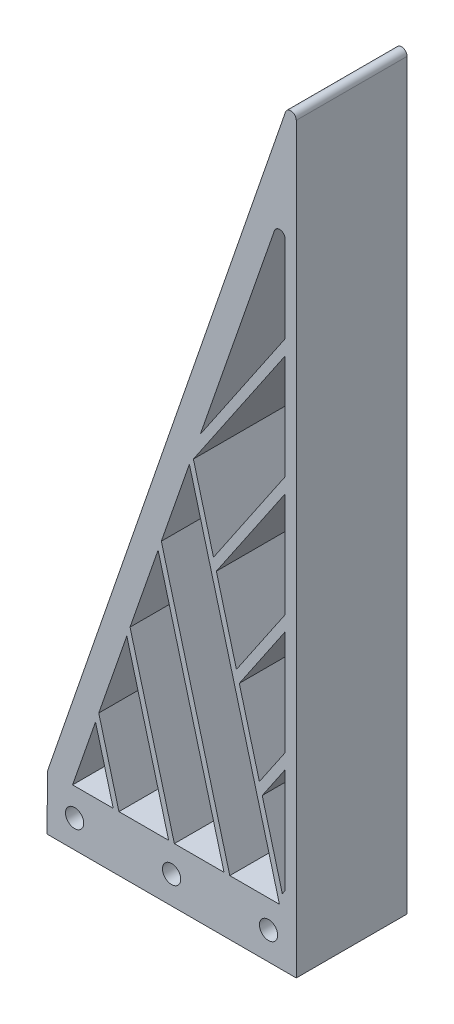
SolidWorks part; units mm, degrees
material "Custom Plastic"
ref_plane "Front Plane" through (0, 0, 0) normal (0, 0, 1) x (1, 0, 0)
ref_plane "Top Plane" through (0, 0, 0) normal (0, 1, 0) x (1, 0, 0)
ref_plane "Right Plane" through (0, 0, 0) normal (1, 0, 0) x (0, 0, -1)
sketch "Sketch1" plane through (0, 0, 0) normal (0, 1, 0) x (1, 0, 0)
  line L1 (-9.5, 8) -> (9.5, 8) construction
  line L2 (-9.5, 8) -> (-9.5, -8) construction
  line L3 (-9.5, -8) -> (9.5, -8) construction
  line L4 (9.5, 8) -> (9.5, -8) construction
  line L5 (-9.5, 8) -> (9.5, -8) construction
  line L6 (-9.5, -8) -> (9.5, 8) construction
  line L7 (12, 10.5) -> (-12, 10.5)
  line L8 (12, 10.5) -> (12, -10.5)
  line L9 (12, -10.5) -> (-12, -10.5)
  line L10 (-12, 10.5) -> (-12, -10.5)
  line L11 (12, 10.5) -> (-12, -10.5) construction
  line L12 (12, -10.5) -> (-12, 10.5) construction
  circle A0 centre (-9.5, 8) radius 1.625
  circle A1 centre (9.5, 8) radius 1.625
  circle A2 centre (9.5, -8) radius 1.625
  circle A3 centre (-9.5, -8) radius 1.625
  point P0 (0, 0)
  point P10 (0, 0)
  dimension "D3" = 3.25
  dimension "D1" = 24
  dimension "D2" = 21
  dimension "D4" = 19
  dimension "D5" = 16
extrude "Boss-Extrude1" [suppressed] add sketch "Sketch1" along normal blind 7.5
sketch "Sketch5" plane through (0, 0, 0) normal (0, 0, 1) x (1, 0, 0)
  line L0 (0, 0) -> (0, 167.0412)
  line L1 (-45, 0) -> (0, 0)
  line L2 (-1.6, 10) -> (-39.8602, 10)
  line L98 (-1.6, 10) -> (-1.6, 153.5644)
  line L99 (-45, 0) -> (-45, 5) construction
  line L102 (-39.9651, 5) -> (-5, 5) construction
  line L103 (-5, 5) -> (-5, 154.3355) construction
  line L104 (0, 0) -> (0, 175) construction
  arc A1 (-3.7727, 167.9673) -> (-45, 0) centre (317.7778, 0) ccw
  arc A24 (-5, 154.3355) -> (-39.8602, 10) centre (317.7778, 0) ccw
  arc A25 (-5, 154.3355) -> (-39.9651, 5) centre (317.7778, 0) ccw construction
  arc A26 (-1.6, 153.5644) -> (-5, 154.3355) centre (-3.3874, 153.5644) ccw
  arc A27 (0, 175) -> (-45, 0) centre (317.7778, 0) ccw construction
  arc A28 (0, 167.0412) -> (-3.7727, 167.9673) centre (-2, 167.0412) ccw
  point P16 (0, 175)
  dimension "D7" = 2
  dimension "D2" = 175
  dimension "D5" = 10
  dimension "D6" = 1.6
  dimension "D1" = 5
  dimension "D3" = 45
  dimension "D4" = 5
extrude "Boss-Extrude4" add sketch "Sketch5" along normal blind 20
sketch "Sketch10" plane through (0, 0, 20) normal (0, 0, 1) x (1, 0, 0)
  line L0 (-39.6854, 15) -> (-1.6, 15)
  line L1 (-1.6, 10) -> (-1.6, 153.5644) construction
  line L2 (-1.6, 16.6) -> (-39.6147, 16.6)
  line L3 (-39.8602, 10) -> (-1.6, 10) construction
  line L4 (0, 10) -> (75, 10) construction
  line L5 (0, 0) -> (0, 167.0412) construction
  line L6 (-38.5345, 26.9605) -> (-0.6577, 22.9795)
  line L7 (-0.4905, 24.5707) -> (-38.2969, 28.5443)
  line L8 (-36.1397, 38.7352) -> (1.1135, 30.8168)
  line L9 (1.4461, 32.3818) -> (-35.7379, 40.2855)
  line L10 (-32.5272, 50.195) -> (3.6942, 38.426)
  line L11 (4.1886, 39.9477) -> (-31.9655, 51.6949)
  line L12 (-27.7367, 61.2145) -> (7.0561, 45.7238)
  line L13 (7.7069, 47.1854) -> (-27.0213, 62.6474)
  line L14 (-21.8205, 71.6728) -> (11.1625, 52.6301)
  line L15 (11.9625, 54.0158) -> (-20.9592, 73.0231)
  line L20 (0, 68.0707) -> (75, 10) construction
  line L21 (-1.6, 69.3095) -> (-28.4662, 90.1114)
  line L22 (-1.6, 70.9537) -> (-28.1077, 91.4779)
  line L23 (3.8607, 75.76) -> (-21.0903, 98.8242)
  line L24 (4.0039, 77.3979) -> (-20.614, 100.1543)
  line L25 (9.8627, 81.7099) -> (-12.9831, 106.861)
  line L26 (10.1482, 83.3291) -> (-12.3927, 108.1445)
  line L27 (16.3605, 87.1142) -> (-4.2063, 114.1607)
  line L28 (16.7861, 88.7023) -> (-3.5063, 115.3878)
  line L29 (23.3046, 91.9315) -> (5.1733, 120.6676)
  line L30 (23.8669, 93.4765) -> (5.9776, 121.8291)
  arc A0 (-5, 154.3355) -> (-39.8602, 10) centre (317.7778, 0) ccw construction
  arc A1 (-5, 154.3355) -> (-39.8602, 10) centre (317.7778, 0) ccw
  point P54 (75, 10)
  point P67 (75, 10)
  dimension "D1" = 1.6
  dimension "D2" = 5
  dimension "D5" = 6
  dimension "D6" = 1.3
  dimension "D9" = 5
  dimension "D7" = 7.75
  dimension "D3" = 144.3355
  dimension "D4" = 6
  dimension "D8" = 5
sketch "Sketch11" plane through (0, 0, 20) normal (0, 0, 1) x (1, 0, 0)
  line L0 (-39.6854, 15) -> (-1.6, 15)
  line L1 (-1.6, 10) -> (-1.6, 153.5644) construction
  line L2 (-1.6, 15) -> (-1.6, 16.6)
  line L3 (-39.6147, 16.6) -> (-1.6, 16.6)
  line L4 (-38.9792, 27.0072) -> (-1.6, 23.0785)
  line L5 (-38.5345, 26.9605) -> (-0.6577, 22.9795) construction
  line L6 (-38.8548, 28.603) -> (-1.6, 24.6873)
  line L7 (-0.4905, 24.5707) -> (-38.2969, 28.5443) construction
  line L8 (-37.857, 39.1002) -> (-1.6, 31.3935)
  line L9 (-37.6777, 40.6978) -> (-1.6, 33.0293)
  line L10 (1.4461, 32.3818) -> (-35.7379, 40.2855) construction
  line L11 (-36.1397, 38.7352) -> (1.1135, 30.8168) construction
  line L12 (-36.2862, 51.4164) -> (-1.6, 40.1462)
  line L13 (-32.5272, 50.195) -> (3.6942, 38.426) construction
  line L14 (-36.0493, 53.0218) -> (-1.6, 41.8285)
  line L15 (4.1886, 39.9477) -> (-31.9655, 51.6949) construction
  line L16 (-34.2115, 64.0973) -> (-1.6, 49.5777)
  line L17 (-27.7367, 61.2145) -> (7.0561, 45.7238) construction
  line L18 (-33.913, 65.7158) -> (-1.6, 51.3291)
  line L19 (7.7069, 47.1854) -> (-27.0213, 62.6474) construction
  line L29 (-28.4662, 90.1114) -> (-1.6, 69.3095)
  line L31 (-28.1077, 91.4779) -> (-1.6, 70.9537)
  line L33 (-1.6, 61.8461) -> (-31.1856, 78.9273)
  line L35 (-31.5516, 77.2911) -> (-1.6, 59.9985)
  line L36 (-25.0168, 102.4538) -> (-1.6, 80.8077)
  line L37 (3.8607, 75.76) -> (-21.0903, 98.8242) construction
  line L38 (-24.5999, 103.8387) -> (-1.6, 82.578)
  line L39 (4.0039, 77.3979) -> (-20.614, 100.1543) construction
  line L40 (-20.8402, 115.511) -> (-1.6, 94.3293)
  line L41 (9.8627, 81.7099) -> (-12.9831, 106.861) construction
  line L42 (-20.3584, 116.914) -> (-1.6, 96.2628)
  line L43 (10.1482, 83.3291) -> (-12.3927, 108.1445) construction
  line L44 (-15.7847, 129.387) -> (-1.6, 110.7332)
  line L45 (16.3605, 87.1142) -> (-4.2063, 114.1607) construction
  line L46 (-15.2308, 130.8061) -> (-1.6, 112.8809)
  line L47 (16.7861, 88.7023) -> (-3.5063, 115.3878) construction
  line L48 (-1.6, 23.0785) -> (-1.6, 24.6873)
  line L49 (-1.6, 31.3935) -> (-1.6, 33.0293)
  line L50 (-1.6, 40.1462) -> (-1.6, 41.8285)
  line L51 (-1.6, 49.5777) -> (-1.6, 51.3291)
  line L53 (-1.6, 110.7332) -> (-1.6, 112.8809)
  line L54 (-1.6, 94.3293) -> (-1.6, 96.2628)
  line L55 (-1.6, 80.8077) -> (-1.6, 82.578)
  line L59 (-21.8205, 71.6728) -> (11.1625, 52.6301) construction
  line L60 (11.9625, 54.0158) -> (-20.9592, 73.0231) construction
  line L61 (-1.6, 59.9985) -> (-1.6, 61.8461)
  line L62 (-9.6623, 144.1803) -> (-1.6, 131.4025)
  line L63 (-9.0282, 145.6117) -> (-1.6, 133.8387)
  line L64 (23.8669, 93.4765) -> (5.9776, 121.8291) construction
  line L65 (23.3046, 91.9315) -> (5.1733, 120.6676) construction
  line L66 (-1.6, 133.8387) -> (-1.6, 131.4025)
  arc A0 (-5, 154.3355) -> (-39.8602, 10) centre (317.7778, 0) ccw construction
  arc A2 (-39.6147, 16.6) -> (-39.6854, 15) centre (317.7778, 0) ccw
  arc A8 (-24.5999, 103.8387) -> (-25.0168, 102.4538) centre (317.7778, 0) ccw
  arc A13 (-9.0282, 145.6117) -> (-9.6623, 144.1803) centre (317.7778, 0) ccw
  arc A14 (-39.6147, 16.6) -> (-39.6854, 15) centre (317.7778, 0) ccw
  arc A15 (-38.8548, 28.603) -> (-38.9792, 27.0072) centre (317.7778, 0) ccw
  arc A16 (-37.6777, 40.6978) -> (-37.857, 39.1002) centre (317.7778, 0) ccw
  arc A17 (-36.0493, 53.0218) -> (-36.2862, 51.4164) centre (317.7778, 0) ccw
  arc A18 (-33.913, 65.7158) -> (-34.2115, 64.0973) centre (317.7778, 0) ccw
  arc A19 (-31.1856, 78.9273) -> (-31.5516, 77.2911) centre (317.7778, 0) ccw
  arc A20 (-28.1077, 91.4779) -> (-28.4662, 90.1114) centre (317.7778, 0) ccw
  arc A21 (-24.5999, 103.8387) -> (-25.0168, 102.4538) centre (317.7778, 0) ccw
  arc A22 (-20.3584, 116.914) -> (-20.8402, 115.511) centre (317.7778, 0) ccw
  arc A23 (-15.2308, 130.8061) -> (-15.7847, 129.387) centre (317.7778, 0) ccw
sketch "Sketch12" plane through (0, 0, 20) normal (0, 0, 1) x (1, 0, 0)
  line L0 (-40, 5) -> (-22.5, 5) construction
  line L1 (-39.8602, 10) -> (-1.6, 10) construction
  line L2 (-22.5, 0) -> (-22.5, 10) construction
  line L3 (-45, 0) -> (0, 0) construction
  line L4 (-22.5, 5) -> (-5, 5) construction
  line L6 (-5, 5) -> (0, 5) construction
  line L7 (0, 0) -> (0, 167.0412) construction
  circle A1 centre (-40, 5) radius 1.65
  circle A2 centre (-22.5, 5) radius 1.65
  circle A3 centre (-5, 5) radius 1.65
  dimension "D1" = 3.3
  dimension "D2" = 17.5
extrude "Cut-Extrude1" cut sketch "Sketch12" against normal through all
sketch "Sketch14" plane through (0, 0, 20) normal (0, 0, 1) x (1, 0, 0)
  line L0 (-1.6, 10) -> (-1.6, 153.5644) construction
  line L2 (-31.6, 158.5644) -> (-1.6, 10)
  line L3 (-31.6, 158.5644) -> (-33.0703, 158.2675)
  line L4 (-1.6, 10) -> (-3.0703, 9.7031)
  line L5 (-33.0703, 158.2675) -> (-3.0703, 9.7031)
  dimension "D1" = 30
  dimension "D2" = 5
  dimension "D3" = 1.5
extrude "Boss-Extrude5" add sketch "Sketch14" against normal blind 20
sketch "Sketch17" plane through (0, 0, 20) normal (0, 0, 1) x (1, 0, 0)
  line L0 (-45, 0) -> (0, 0)
  line L1 (0, 0) -> (0, 167.0412)
  line L2 (-120.6382, 868.826) -> (-109.1292, -31.174)
  line L3 (-109.1292, -31.174) -> (790.8708, -19.665)
  line L4 (790.8708, -19.665) -> (784.1337, 507.1754)
  line L5 (784.1337, 507.1754) -> (-120.6382, 868.826)
  arc A1 (0, 167.0412) -> (-3.7727, 167.9673) centre (-2, 167.0412) ccw
  arc A3 (-3.7727, 167.9673) -> (-45, 0) centre (317.7778, 0) ccw
  dimension "D1" = 900
  dimension "D2" = 900
extrude "Cut-Extrude2" cut sketch "Sketch17" against normal blind 20
sketch "Sketch18" plane through (0, 0, 20) normal (0, 0, 1) x (1, 0, 0)
  line L0 (-45, 0) -> (0, 0)
  line L1 (0, 0) -> (0, 167.0412)
  line L2 (10.5677, -7.1526) -> (26.572, 318.7821)
  line L3 (26.572, 318.7821) -> (-234.7297, 306.4711)
  line L4 (-234.7297, 306.4711) -> (-205.7988, -46.8557)
  line L5 (-205.7988, -46.8557) -> (10.5677, -7.1526)
  arc A0 (0, 167.0412) -> (-3.7727, 167.9673) centre (-2, 167.0412) ccw
  arc A1 (-3.7727, 167.9673) -> (-45, 0) centre (317.7778, 0) ccw
extrude "Cut-Extrude3" cut sketch "Sketch18" against normal blind 30
pattern_linear "LPattern2" count 5 spacing 8 along (0.9802, 0.1979, 0) count 5 spacing 8 along (-0.9802, -0.1979, 0) of "Boss-Extrude5"
sketch "Sketch19" plane through (0, 0, 20) normal (0, 0, 1) x (1, 0, 0)
  line L0 (-45, 0) -> (0, 0)
  line L1 (0, 0) -> (0, 167.0412)
  line L2 (-113.91, -19.1316) -> (183.2467, -29.1763)
  line L3 (183.2467, -29.1763) -> (134.6972, 220.2679)
  line L4 (134.6972, 220.2679) -> (-171.2487, 235.335)
  line L5 (-171.2487, 235.335) -> (-113.91, -19.1316)
  arc A0 (0, 167.0412) -> (-3.7727, 167.9673) centre (-2, 167.0412) ccw
  arc A1 (-3.7727, 167.9673) -> (-45, 0) centre (317.7778, 0) ccw
extrude "Cut-Extrude4" cut sketch "Sketch19" against normal blind 30
sketch "Sketch22" plane through (0, 0, 20) normal (0, 0, 1) x (1, 0, 0)
  line L1 (-39.8602, 10) -> (15.1197, 10)
  line L2 (-39.8602, 142.3247) -> (-39.8602, 170.8288)
  line L3 (-39.8602, 170.8288) -> (15.1197, 170.8288)
  line L4 (15.1197, 10) -> (15.1197, 170.8288)
  line L5 (-39.8602, 10) -> (-80.8105, 10)
  line L7 (-39.8602, 142.3247) -> (-80.8105, 142.3247)
  line L8 (-80.8105, 10) -> (-80.8105, 142.3247)
extrude "Cut-Extrude5" cut sketch "Sketch22" against normal blind 20
sketch "Sketch24" plane through (0, 0, 20) normal (0, 0, 1) x (1, 0, 0)
  line L0 (0, 10) -> (0, 140)
  line L1 (0, 140) -> (-44.8621, 10)
  line L2 (0, 10) -> (-2, 10)
  line L3 (-2, 10) -> (-2, 120.4099)
  line L4 (-2, 120.4099) -> (-40.3621, 10)
  line L5 (-40.3621, 10) -> (-44.8621, 10)
  line L6 (0, 0) -> (0, 10) construction
  dimension "D1" = 2
  dimension "D2" = 4.5
  dimension "D3" = 4.5
  dimension "D4" = 130
  dimension "D5" = 180
extrude "Boss-Extrude7" add sketch "Sketch24" against normal blind 20
sketch "Sketch26" plane through (0, 0, 20) normal (0, 0, 1) x (1, 0, 0)
  line L0 (-2, 10) -> (-2.9659, 9.7412)
  line L1 (-2, 10) -> (-28.5498, 109.0851)
  line L2 (-2.9659, 9.7412) -> (-29.5157, 108.8262)
  line L3 (-28.5498, 109.0851) -> (-29.5157, 108.8262)
  line L5 (-2, 120.4099) -> (-2, 10) construction
  dimension "D1" = 1
  dimension "D2" = 15
extrude "Boss-Extrude8" add sketch "Sketch26" against normal blind 20
pattern_linear "LPattern3" count 4 spacing 10 along (-1, 0, 0) of "Boss-Extrude8"
sketch "Sketch27" plane through (0, 0, 20) normal (0, 0, 1) x (1, 0, 0)
  line L2 (-2, 10) -> (63.7411, 106.8809)
  line L3 (-2, 10) -> (-3.2412, 10.8423)
  line L4 (63.7411, 106.8809) -> (62.4999, 107.7231)
  line L5 (-3.2412, 10.8423) -> (62.4999, 107.7231)
  line L6 (-18.7031, 72.3368) -> (-2, 120.4099) construction
  dimension "D1" = 1.5
  dimension "D2" = 15
extrude "Boss-Extrude9" add sketch "Sketch27" against normal blind 20
pattern_linear "LPattern4" count 5 spacing 16 along (-0.2588, 0.9659, 0) of "Boss-Extrude9"
sketch "Sketch28" plane through (0, 0, 20) normal (0, 0, 1) x (1, 0, 0)
  line L0 (0, 140) -> (-44.8621, 10)
  line L1 (-44.8621, 10) -> (-45, 0)
  line L2 (-45, 0) -> (0, 0)
  line L3 (0, 0) -> (0, 140)
  line L4 (34.1496, 213.6258) -> (124.5075, 99.3298)
  line L5 (124.5075, 99.3298) -> (18.3033, -39.9157)
  line L6 (18.3033, -39.9157) -> (-70.0521, -38.6977)
  line L7 (-70.0521, -38.6977) -> (-140.1602, 173.5042)
  line L8 (-140.1602, 173.5042) -> (34.1496, 213.6258)
extrude "Cut-Extrude6" cut sketch "Sketch28" against normal blind 20
fillet "Fillet4" radius 1 2 edges at (0, 140, 10) (-2, 120.4099, 10)
equation "\"Middle Finger Width\"= 30mm"
equation "\"Finger Length\"= 45"
equation "\"Finger Height\"= \"Finger Length\" * 3.5"
equation "\"D3@Sketch5\"=\"Finger Length\""
equation "\"Base Height\"= 10mm"
equation "\"D1@Sketch5\"= \"Base Height\" / 2"
equation "\"D5@Sketch5\"= \"Base Height\""
equation "\"Thick Walls\"= 1.6mm"
equation "\"Thin Walls\"= 1.3mm"
equation "\"D6@Sketch5\"=\"Thick Walls\""
equation "\"D2@Sketch10\"=\"Base Height\"/2"
equation "\"D1@Sketch10\"=\"Thick Walls\" "
equation "\"D6@Sketch10\"=\"Thin Walls\""
equation "\"D1@Boss-Extrude4\"  = 2 * \"Middle Finger Width\" /3"
equation "\"Outer Finger Width\"= 2 * \"Middle Finger Width\" / 3"
